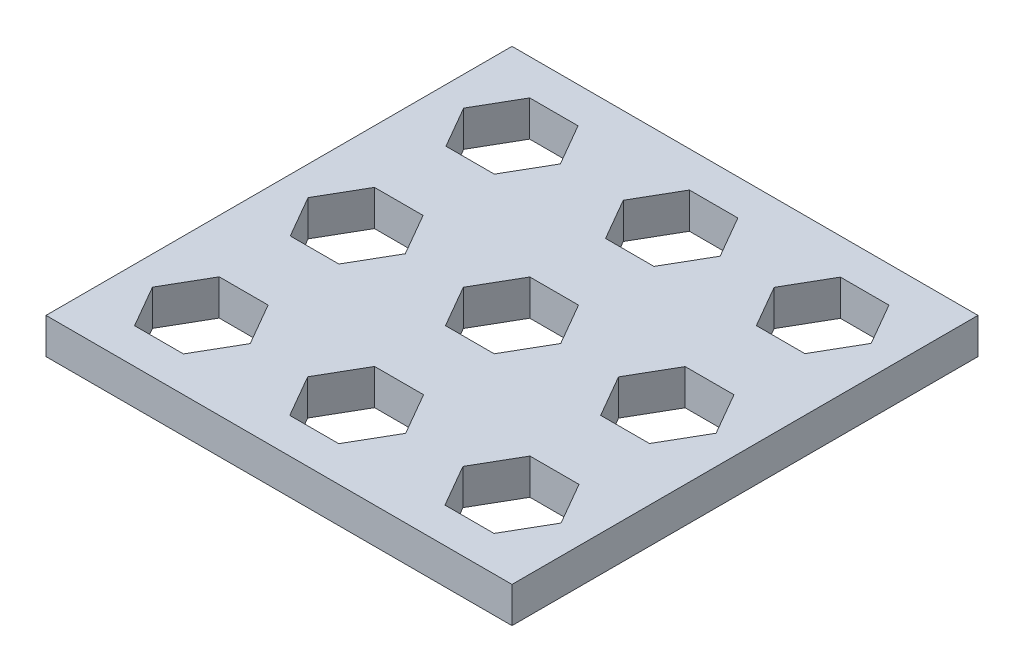
SolidWorks part; units mm, degrees
ref_plane "Front Plane" through (0, 0, 0) normal (0, 0, 1) x (1, 0, 0)
ref_plane "Top Plane" through (0, 0, 0) normal (0, 1, 0) x (1, 0, 0)
ref_plane "Right Plane" through (0, 0, 0) normal (1, 0, 0) x (0, 0, -1)
sketch "Sketch1" plane through (0, 0, 0) normal (0, 1, 0) x (1, 0, 0)
  line L1 (-15, -15) -> (15, -15)
  line L2 (-15, -15) -> (-15, 15)
  line L3 (-15, 15) -> (15, 15)
  line L4 (15, -15) -> (15, 15)
  line L5 (-15, -15) -> (15, 15) construction
  line L6 (-15, 15) -> (15, -15) construction
  point P0 (0, 0)
  dimension "D1" = 30
  dimension "D2" = 30
extrude "Boss-Extrude1" add sketch "Sketch1" along normal blind 2.3
sketch "Sketch2" plane through (0, 2.3, 0) normal (0, 1, 0) x (1, 0, 0)
  line L1 (3.135, 0) -> (1.5675, 2.715)
  line L2 (1.5675, 2.715) -> (-1.5675, 2.715)
  line L3 (-1.5675, 2.715) -> (-3.135, 0)
  line L4 (-3.135, 0) -> (-1.5675, -2.715)
  line L5 (-1.5675, -2.715) -> (1.5675, -2.715)
  line L6 (1.5675, -2.715) -> (3.135, 0)
  line L79 (-6.8881, 10) -> (-8.444, 12.695)
  line L80 (-8.444, 12.695) -> (-11.556, 12.695)
  line L81 (-11.556, 12.695) -> (-13.1119, 10)
  line L82 (-13.1119, 10) -> (-11.556, 7.305)
  line L83 (-11.556, 7.305) -> (-8.444, 7.305)
  line L84 (-8.444, 7.305) -> (-6.8881, 10)
  line L85 (3.3988, 10) -> (1.8399, 12.7)
  line L86 (1.8399, 12.7) -> (-1.2778, 12.7)
  line L87 (-1.2778, 12.7) -> (-2.8366, 10)
  line L88 (-2.8366, 10) -> (-1.2778, 7.3)
  line L89 (-1.2778, 7.3) -> (1.8399, 7.3)
  line L90 (1.8399, 7.3) -> (3.3988, 10)
  line L91 (13.1224, 10) -> (11.5606, 12.705)
  line L92 (11.5606, 12.705) -> (8.4372, 12.705)
  line L93 (8.4372, 12.705) -> (6.8754, 10)
  line L94 (6.8754, 10) -> (8.4372, 7.295)
  line L95 (8.4372, 7.295) -> (11.5606, 7.295)
  line L96 (11.5606, 7.295) -> (13.1224, 10)
  line L97 (13.1397, 0) -> (11.5693, 2.72)
  line L98 (11.5693, 2.72) -> (8.4285, 2.72)
  line L99 (8.4285, 2.72) -> (6.8581, 0)
  line L100 (6.8581, 0) -> (8.4285, -2.72)
  line L101 (8.4285, -2.72) -> (11.5693, -2.72)
  line L102 (11.5693, -2.72) -> (13.1397, 0)
  line L103 (13.157, -10) -> (11.578, -7.265)
  line L104 (11.578, -7.265) -> (8.4199, -7.265)
  line L105 (8.4199, -7.265) -> (6.8408, -10)
  line L106 (6.8408, -10) -> (8.4199, -12.735)
  line L107 (8.4199, -12.735) -> (11.578, -12.735)
  line L108 (11.578, -12.735) -> (13.157, -10)
  line L109 (3.1523, -10) -> (1.5762, -7.27)
  line L110 (1.5762, -7.27) -> (-1.5762, -7.27)
  line L111 (-1.5762, -7.27) -> (-3.1523, -10)
  line L112 (-3.1523, -10) -> (-1.5762, -12.73)
  line L113 (-1.5762, -12.73) -> (1.5762, -12.73)
  line L114 (1.5762, -12.73) -> (3.1523, -10)
  line L115 (-6.8534, -10) -> (-8.4267, -7.275)
  line L116 (-8.4267, -7.275) -> (-11.5733, -7.275)
  line L117 (-11.5733, -7.275) -> (-13.1466, -10)
  line L118 (-13.1466, -10) -> (-11.5733, -12.725)
  line L119 (-11.5733, -12.725) -> (-8.4267, -12.725)
  line L120 (-8.4267, -12.725) -> (-6.8534, -10)
  line L121 (-6.8708, 0) -> (-8.4354, 2.71)
  line L122 (-8.4354, 2.71) -> (-11.5646, 2.71)
  line L123 (-11.5646, 2.71) -> (-13.1292, 0)
  line L124 (-13.1292, 0) -> (-11.5646, -2.71)
  line L125 (-11.5646, -2.71) -> (-8.4354, -2.71)
  line L126 (-8.4354, -2.71) -> (-6.8708, 0)
  circle A0 centre (0, 0) radius 2.715 construction
  circle A1 centre (-10, 10) radius 2.695 construction
  circle A2 centre (0.2811, 10) radius 2.7 construction
  circle A3 centre (9.9989, 10) radius 2.705 construction
  circle A4 centre (9.9989, 0) radius 2.72 construction
  circle A5 centre (9.9989, -10) radius 2.735 construction
  circle A6 centre (0, -10) radius 2.73 construction
  circle A7 centre (-10, -10) radius 2.725 construction
  circle A8 centre (-10, 0) radius 2.71 construction
  point P1 (0, -2.715)
  point P12 (0.2811, 7.3)
  dimension "D1" = 5.43
  dimension "D2" = 5.42
  dimension "D3" = 5.41
  dimension "D4" = 5.4
  dimension "D5" = 5.39
  dimension "5.2" = 5.44
  dimension "D7" = 5.45
  dimension "D8" = 5.46
  dimension "D9" = 5.47
extrude "Cut-Extrude3" cut sketch "Sketch2" against normal blind 2.3
